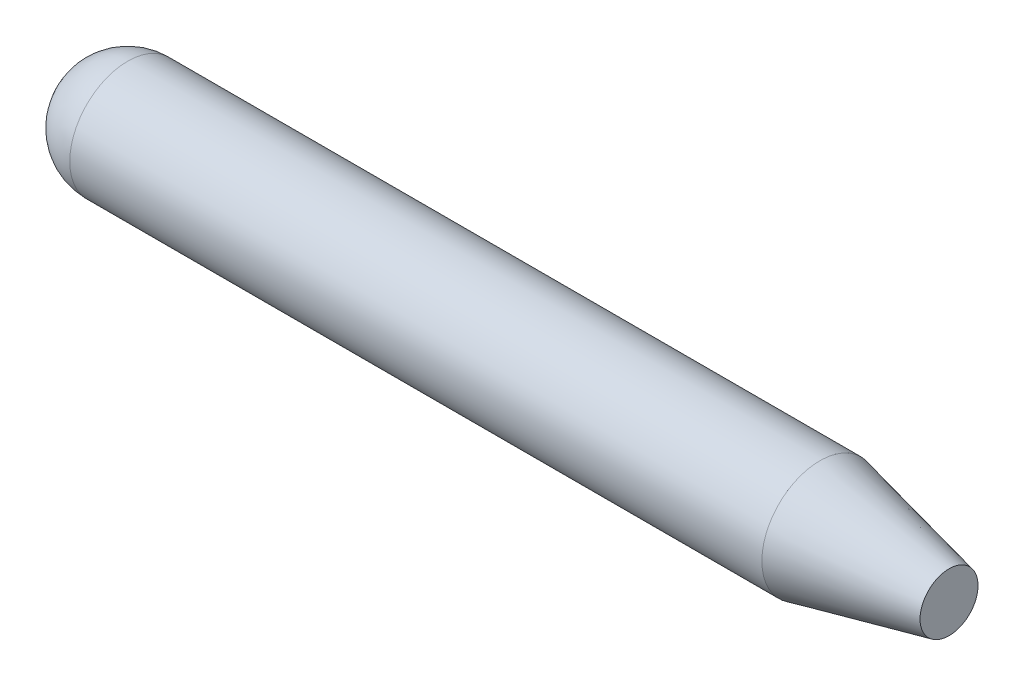
SolidWorks part; units mm, degrees
ref_plane "Front Plane" through (0, 0, 0) normal (0, 0, 1) x (1, 0, 0)
ref_plane "Top Plane" through (0, 0, 0) normal (0, 1, 0) x (1, 0, 0)
ref_plane "Right Plane" through (0, 0, 0) normal (1, 0, 0) x (0, 0, -1)
sketch "Sketch1" plane through (0, 0, 0) normal (0, 0, 1) x (1, 0, 0)
  line L0 (0, 0) -> (1040.2752, 0) construction
  line L1 (68.58, 68.58) -> (887.4078, 68.58)
  line L2 (887.4078, 68.58) -> (1040.2752, 34.3254)
  line L3 (1040.2752, 34.3254) -> (1040.2752, 0)
  line L4 (0, 0) -> (1040.2752, 0)
  arc A0 (68.58, 68.58) -> (0, 0) centre (68.58, 0) ccw
  dimension "D1" = 68.58
revolve "Revolve1" add sketch "Sketch1" angle 360 about L0
move or copy body "Body-Move/Copy1" bodies to move or copy 101 copy no translate (-518.16, 0, 0)
